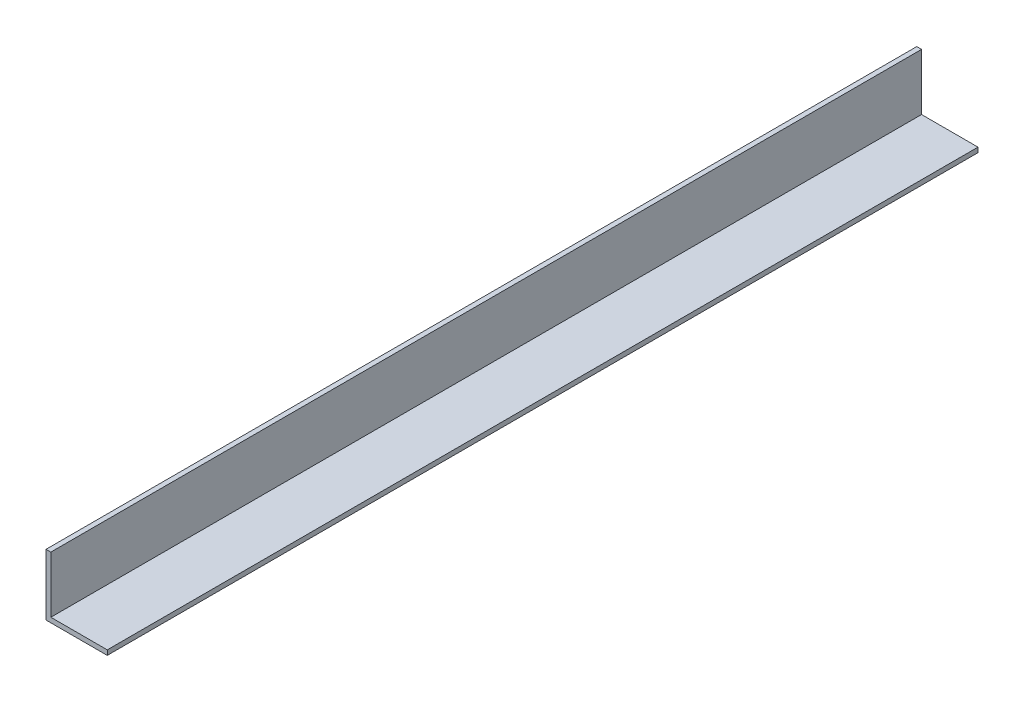
SolidWorks part; units mm, degrees
ref_plane "Alzado" through (0, 0, 0) normal (0, 0, 1) x (1, 0, 0)
ref_plane "Planta" through (0, 0, 0) normal (0, 1, 0) x (1, 0, 0)
ref_plane "Vista lateral" through (0, 0, 0) normal (1, 0, 0) x (0, 0, -1)
sketch "Croquis1" plane through (0, 0, 0) normal (0, 0, 1) x (1, 0, 0)
  line L0 (0, 0) -> (0, 25.4)
  line L1 (0, 25.4) -> (2, 25.4)
  line L2 (2, 25.4) -> (2, 2)
  line L3 (2, 2) -> (25.4, 2)
  line L4 (25.4, 2) -> (25.4, 0)
  line L5 (25.4, 0) -> (0, 0)
  dimension "D1" = 2
  dimension "D2" = 2
  dimension "D3" = 25.4
  dimension "D4" = 25.4
extrude "Saliente-Extruir1" add sketch "Croquis1" along normal blind 361
